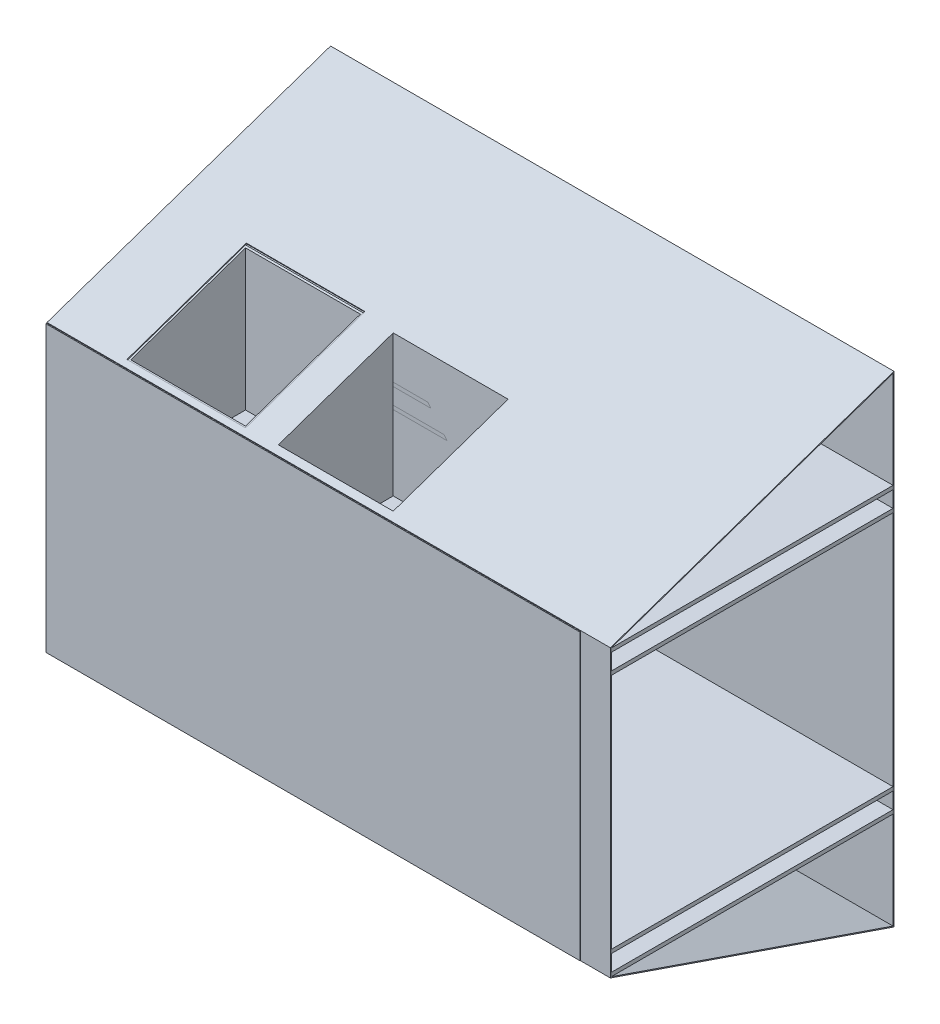
SolidWorks part; units mm, degrees
material "Stainless Steel 2205"
ref_plane "Front Plane" through (0, 0, 0) normal (0, 0, 1) x (1, 0, 0)
ref_plane "Top Plane" through (0, 0, 0) normal (0, 1, 0) x (1, 0, 0)
ref_plane "Right Plane" through (0, 0, 0) normal (1, 0, 0) x (0, 0, -1)
sketch "Sketch1" plane through (0, 0, 0) normal (0, 0, 1) x (1, 0, 0)
  line L1 (0, 0) -> (1800, 0)
  line L2 (0, 0) -> (0, -960)
  line L3 (0, -960) -> (1800, -960)
  line L4 (1800, 0) -> (1800, -960)
  dimension "D1" = 1800
  dimension "D2" = 960
extrude "Boss-Extrude1" add sketch "Sketch1" along normal blind 6.35
sketch "Sketch2" plane through (0, 0, 0) normal (1, 0, 0) x (0, 0, -1)
  line L0 (0, 0) -> (950, 327.1112)
  line L1 (950, 327.1112) -> (950, -1287.1112)
  line L2 (950, -1287.1112) -> (0, -960)
  line L3 (0, -960) -> (0, 0)
  line L4 (-3.175, -962.2647) -> (-3.175, 2.2647)
  line L5 (-3.175, 2.2647) -> (953.175, 331.5624)
  line L6 (953.175, 331.5624) -> (953.175, -1291.5624)
  line L7 (953.175, -1291.5624) -> (-3.175, -962.2647)
  dimension "D2" = 71
  dimension "D3" = 71
  dimension "D4" = 950
  dimension "D1" = 3.175
extrude "Boss-Extrude2" add sketch "Sketch2" along normal blind 1900
sketch "Sketch4" plane through (0, 0, 0) normal (0, 1, 0) x (1, 0, 0)
  line L0 (0, 953.175) -> (0, -3.175) construction
  line L1 (249.6312, 417.8713) -> (649.6312, 417.8713)
  line L2 (249.6312, 417.8713) -> (249.6312, 17.8713)
  line L3 (249.6312, 17.8713) -> (649.6312, 17.8713)
  line L4 (649.6312, 417.8713) -> (649.6312, 17.8713)
  dimension "D1" = 400
  dimension "D2" = 400
  dimension "D3" = 249.6312
curve "Curve1"
sketch "Sketch6" plane through (0, 3.002, 1.0337) normal (0, 0.9455, 0.3256) x (1, 0, 0)
  line L0 (649.6312, 441.9494) -> (649.6312, 18.9011) construction
  line L1 (649.6312, 444.6894) -> (249.6312, 444.6894)
  line L2 (649.6312, 444.6894) -> (649.6312, 18.9011)
  line L3 (649.6312, 18.9011) -> (249.6312, 18.9011)
  line L4 (249.6312, 444.6894) -> (249.6312, 18.9011)
  line L5 (649.6312, 18.9011) -> (249.6312, 18.9011) construction
extrude "Cut-Extrude1" cut sketch "Sketch6" against normal blind 300
sketch "Sketch7" plane through (0, -861.2472, 296.5512) normal (0, -0.9455, 0.3256) x (1, 0, 0)
  line L0 (249.6312, -331.4465) -> (249.6312, -754.4948) construction
  line L1 (249.6312, -796.9701) -> (649.6312, -796.9701)
  line L2 (249.6312, -796.9701) -> (249.6312, -371.299)
  line L3 (249.6312, -371.299) -> (649.6312, -371.299)
  line L4 (649.6312, -796.9701) -> (649.6312, -371.299)
  line L5 (649.6312, -754.4948) -> (649.6312, -331.4465) construction
extrude "Cut-Extrude2" cut sketch "Sketch7" against normal blind 300
sketch "Sketch8" plane through (0, 0, 0) normal (0, 1, 0) x (1, 0, 0)
  line L0 (255.9812, 23.1876) -> (255.9812, 410.4876)
  line L1 (249.6312, 16.8376) -> (649.6312, 16.8376)
  line L2 (249.6312, 16.8376) -> (249.6312, 416.8376)
  line L3 (249.6312, 416.8376) -> (649.6312, 416.8376)
  line L4 (649.6312, 16.8376) -> (649.6312, 416.8376)
  line L5 (255.9812, 410.4876) -> (643.2812, 410.4876)
  line L6 (643.2812, 23.1876) -> (643.2812, 410.4876)
  line L7 (255.9812, 23.1876) -> (643.2812, 23.1876)
  dimension "D1" = 6.35
extrude "Boss-Extrude4" add sketch "Sketch8" against normal up to surface and the other way up to surface separate body up to face at (449.6312, -1048.4208, -256.7926) other way up to face at (449.6312, 75.4651, -219.1667)
sketch "Sketch11" plane through (0, 0, -953.175) normal (0, 0, -1) x (-1, 0, 0)
  line L2 (-1900, 331.5624) -> (0, 331.5624) construction
  line L3 (0, -1291.5624) -> (0, 331.5624) construction
  circle A1 centre (-350, -492.2076) radius 131.35
  dimension "D1" = 823.77
  dimension "D2" = 350
extrude "Boss-Extrude6" add sketch "Sketch11" against normal blind 30
sketch "Sketch12" plane through (0, 0, -953.175) normal (0, 0, -1) x (-1, 0, 0)
  line L0 (0, -1291.5624) -> (0, 331.5624) construction
  line L2 (-1900, 331.5624) -> (0, 331.5624) construction
  circle A0 centre (-350, -492.2076) radius 125
  dimension "D1" = 250
  dimension "D2" = 350
  dimension "D3" = 823.77
extrude "Cut-Extrude5" cut sketch "Sketch12" against normal blind 20
sketch "Sketch14" plane through (0, 0, 0) normal (0, 1, 0) x (1, 0, 0)
  line L0 (649.6312, 417.8713) -> (649.6312, 17.8713) construction
  line L1 (749.6312, 412.7618) -> (1149.6312, 412.7618)
  line L2 (749.6312, 412.7618) -> (749.6312, 12.7618)
  line L3 (749.6312, 12.7618) -> (1149.6312, 12.7618)
  line L4 (1149.6312, 412.7618) -> (1149.6312, 12.7618)
  line L5 (755.9812, 406.4118) -> (1143.2812, 406.4118)
  line L6 (1143.2812, 406.4118) -> (1143.2812, 19.1118)
  line L7 (755.9812, 19.1118) -> (1143.2812, 19.1118)
  line L8 (755.9812, 406.4118) -> (755.9812, 19.1118)
  dimension "D1" = 400
  dimension "D2" = 400
  dimension "D3" = 100
  dimension "D4" = 6.35
extrude "Boss-Extrude7" add sketch "Sketch14" along normal up to next and the other way up to next
sketch "Sketch15" plane through (0, 0, 0) normal (0, 1, 0) x (1, 0, 0)
  line L5 (755.9812, 408.5123) -> (1143.2812, 408.5123)
  line L6 (1143.2812, 408.5123) -> (1143.2812, 21.2123)
  line L7 (755.9812, 21.2123) -> (1143.2812, 21.2123)
  line L8 (755.9812, 408.5123) -> (755.9812, 21.2123)
extrude "Cut-Extrude6" cut sketch "Sketch15" against normal up to next and the other way up to next
sketch "Sketch16" plane through (249.6312, 0, 0) normal (-1, 0, 0) x (0, 0, 1)
  line L0 (-416.8376, -1103.5287) -> (-416.8376, 143.5287) construction
  line L1 (-416.8376, -332.1987) -> (-16.8376, -332.1987)
  line L2 (-416.8376, -332.1987) -> (-416.8376, -532.1987)
  line L3 (-416.8376, -532.1987) -> (-16.8376, -532.1987)
  line L4 (-16.8376, -332.1987) -> (-16.8376, -532.1987)
  line L5 (-16.8376, -965.7977) -> (-16.8376, 5.7977) construction
  dimension "D1" = 200
  dimension "D2" = 571.33
extrude "Cut-Extrude8" cut sketch "Sketch16" against normal blind 940
sketch "Sketch18" plane through (1149.6312, 0, 0) normal (1, 0, 0) x (0, 0, -1)
  line L0 (12.7618, -964.3942) -> (12.7618, 4.3942) construction
  line L1 (16.8376, -532.1987) -> (12.7618, -532.1987)
  line L2 (16.8376, -532.1987) -> (16.8376, -410.1274)
  line L3 (16.8376, -410.1274) -> (12.7618, -410.1274)
  line L4 (12.7618, -532.1987) -> (12.7618, -410.1274)
extrude "Cut-Extrude9" cut sketch "Sketch18" against normal blind 410
sketch "Sketch19" plane through (0, -332.1987, 0) normal (0, -1, 0) x (1, 0, 0)
  line L1 (1143.2812, -21.2123) -> (755.9812, -21.2123)
  line L2 (1143.2812, -21.2123) -> (1143.2812, -408.5123)
  line L3 (1143.2812, -408.5123) -> (755.9812, -408.5123)
  line L4 (755.9812, -21.2123) -> (755.9812, -408.5123)
extrude "Boss-Extrude22" add sketch "Sketch19" along normal blind 10 separate body
sketch "Sketch22" plane through (0, -532.1987, 0) normal (0, 1, 0) x (1, 0, 0)
  line L1 (1143.2812, 408.5123) -> (755.9812, 408.5123)
  line L2 (1143.2812, 408.5123) -> (1143.2812, 19.1118)
  line L3 (1143.2812, 19.1118) -> (755.9812, 19.1118)
  line L4 (755.9812, 408.5123) -> (755.9812, 19.1118)
extrude "Boss-Extrude24" add sketch "Sketch22" along normal blind 10 separate body
sketch "Sketch23" plane through (0, -532.1987, 0) normal (0, 1, 0) x (1, 0, 0)
  line L1 (643.2812, 410.4876) -> (255.9812, 410.4876)
  line L2 (643.2812, 410.4876) -> (643.2812, 23.1876)
  line L3 (643.2812, 23.1876) -> (255.9812, 23.1876)
  line L4 (255.9812, 410.4876) -> (255.9812, 23.1876)
extrude "Boss-Extrude25" add sketch "Sketch23" along normal blind 10 separate body
sketch "Sketch24" plane through (0, -332.1987, 0) normal (0, -1, 0) x (1, 0, 0)
  line L1 (643.2812, -23.1876) -> (255.9812, -23.1876)
  line L2 (643.2812, -23.1876) -> (643.2812, -410.4876)
  line L3 (643.2812, -410.4876) -> (255.9812, -410.4876)
  line L4 (255.9812, -23.1876) -> (255.9812, -410.4876)
extrude "Boss-Extrude26" add sketch "Sketch24" along normal blind 10 separate body
sketch "Sketch25" plane through (0, 0, 0) normal (1, 0, 0) x (0, 0, -1)
  line L0 (950, -1287.1112) -> (950, 327.1112) construction
  line L1 (0, 0) -> (950, 0)
  line L2 (0, 0) -> (0, -80)
  line L3 (0, -80) -> (950, -80)
  line L4 (950, 0) -> (950, -80)
  line L5 (950, -1287.1112) -> (950, 327.1112) construction
  line L6 (0, -960) -> (950, -960)
  line L7 (0, -960) -> (0, -880)
  line L8 (0, -880) -> (950, -880)
  line L9 (950, -960) -> (950, -880)
  line L10 (0, -67.3) -> (950, -67.3)
  line L11 (0, -67.3) -> (0, -12.7)
  line L12 (0, -12.7) -> (950, -12.7)
  line L13 (950, -67.3) -> (950, -12.7)
  line L15 (0, -892.7) -> (950, -892.7)
  line L16 (0, -892.7) -> (0, -947.3)
  line L17 (0, -947.3) -> (950, -947.3)
  line L18 (950, -892.7) -> (950, -947.3)
  dimension "D1" = 80
  dimension "D2" = 80
  dimension "D3" = 12.7
  dimension "D4" = 12.7
  dimension "D5" = 12.7
  dimension "D6" = 12.7
extrude "Boss-Extrude27" add sketch "Sketch25" along normal blind 1900 contours L17 L7 L6 L9 | L7 L15 L9 L8 | L10 L2 L3 L4 | L2 L12 L4 L1
sketch "Sketch26" plane through (0, 0, 0) normal (0, 1, 0) x (1, 0, 0)
  line L1 (643.2812, 410.4876) -> (255.9812, 410.4876)
  line L2 (643.2812, 410.4876) -> (643.2812, 23.1876)
  line L3 (643.2812, 23.1876) -> (255.9812, 23.1876)
  line L4 (255.9812, 410.4876) -> (255.9812, 23.1876)
extrude "Cut-Extrude10" cut sketch "Sketch26" against normal blind 300
sketch "Sketch27" plane through (0, 0, 0) normal (0, 1, 0) x (1, 0, 0)
  line L1 (1143.2812, 408.5123) -> (755.9812, 408.5123)
  line L2 (1143.2812, 408.5123) -> (1143.2812, 21.2123)
  line L3 (1143.2812, 21.2123) -> (755.9812, 21.2123)
  line L4 (755.9812, 408.5123) -> (755.9812, 21.2123)
extrude "Cut-Extrude11" cut sketch "Sketch27" against normal blind 300
sketch "Sketch28" plane through (0, -960, 0) normal (0, -1, 0) x (1, 0, 0)
  line L1 (1143.2812, -21.2123) -> (755.9812, -21.2123)
  line L2 (1143.2812, -21.2123) -> (1143.2812, -408.5123)
  line L3 (1143.2812, -408.5123) -> (755.9812, -408.5123)
  line L4 (755.9812, -21.2123) -> (755.9812, -408.5123)
extrude "Cut-Extrude12" cut sketch "Sketch28" against normal blind 300
sketch "Sketch29" plane through (0, -960, 0) normal (0, -1, 0) x (1, 0, 0)
  line L1 (643.2812, -23.1876) -> (255.9812, -23.1876)
  line L2 (643.2812, -23.1876) -> (643.2812, -410.4876)
  line L3 (643.2812, -410.4876) -> (255.9812, -410.4876)
  line L4 (255.9812, -23.1876) -> (255.9812, -410.4876)
extrude "Cut-Extrude13" cut sketch "Sketch29" against normal blind 300
sketch "Sketch30" plane through (0, 0, -933.175) normal (0, 0, -1) x (-1, 0, 0)
  line L0 (-350, -492.2076) -> (-225, -492.2076) construction
  line L1 (-350, -492.2076) -> (-261.6117, -403.8192) construction
  circle A0 centre (-350, -492.2076) radius 125
  circle A1 centre (-285, -427.2076) radius 11.1468
  circle A2 centre (-415, -427.2076) radius 11.1468
  circle A3 centre (-415, -557.2076) radius 11.1468
  circle A4 centre (-285, -557.2076) radius 11.1468
  point P7 (0, 0)
  point P16 (-350, -492.2076)
  dimension "D2" = 22.2936
  dimension "D4" = 130
  dimension "D1" = 45
  dimension "D3" = 4
extrude "Cut-Extrude14" cut sketch "Sketch30" against normal up to next (10 mm away) contours A2 | A1 | A4 | A3 | A0
